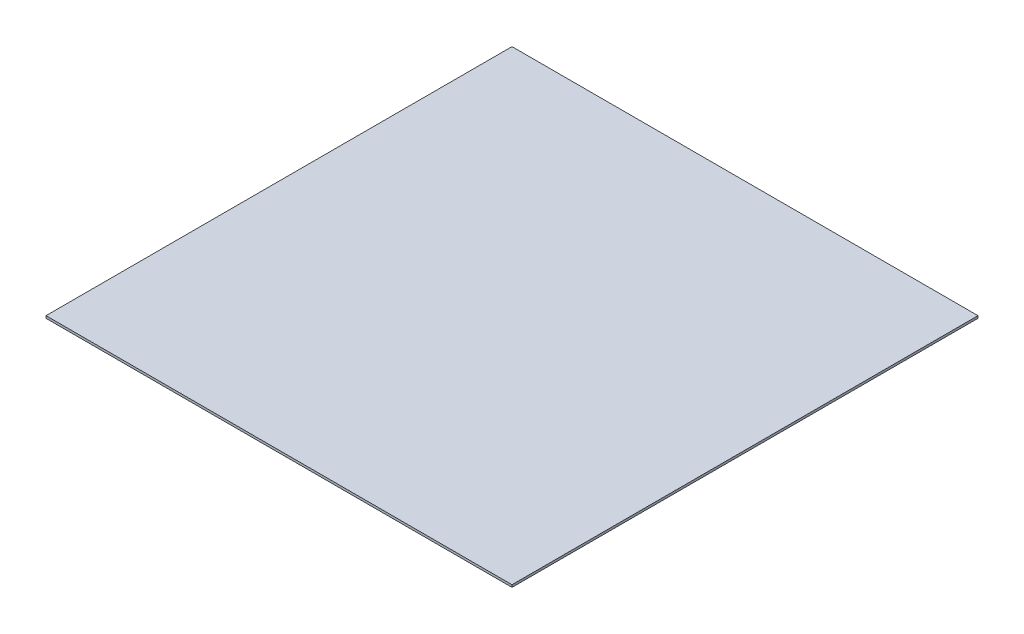
SolidWorks part; units mm, degrees
ref_plane "Front Plane" through (0, 0, 0) normal (0, 0, 1) x (1, 0, 0)
ref_plane "Top Plane" through (0, 0, 0) normal (0, 1, 0) x (1, 0, 0)
ref_plane "Right Plane" through (0, 0, 0) normal (1, 0, 0) x (0, 0, -1)
other "Configuration Table"
sketch "Sketch1" plane through (0, 0, 0) normal (0, 0, 1) x (1, 0, 0)
  line L1 (0, 0) -> (320, 0)
  line L2 (0, 0) -> (0, 1.6)
  line L3 (0, 1.6) -> (320, 1.6)
  line L4 (320, 0) -> (320, 1.6)
extrude "KUTU_taban_320x320_1" add sketch "Sketch1" against normal blind 320 separate body
